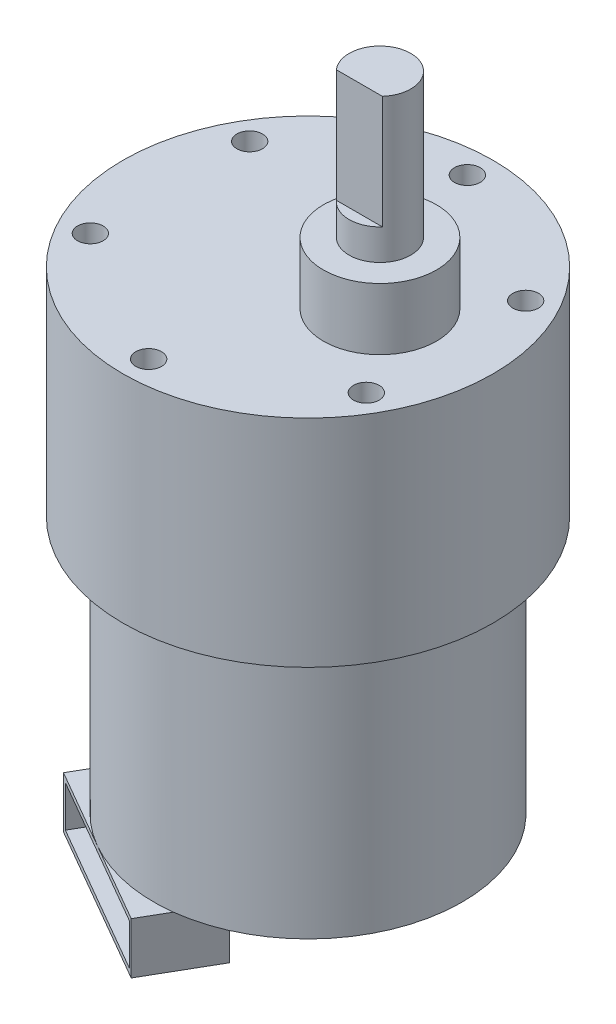
SolidWorks part; units mm, degrees
ref_plane "前视基准面" through (0, 0, 0) normal (0, 0, 1) x (1, 0, 0)
ref_plane "上视基准面" through (0, 0, 0) normal (0, 1, 0) x (1, 0, 0)
ref_plane "右视基准面" through (0, 0, 0) normal (1, 0, 0) x (0, 0, -1)
sketch "草图1" plane through (0, 0, 0) normal (0, 1, 0) x (1, 0, 0)
  circle A0 centre (0, 0) radius 15
  dimension "D1" = 30
extrude "凸台-拉伸1" add sketch "草图1" along normal blind 25
sketch "草图2" plane through (0, 25, 0) normal (0, 1, 0) x (1, 0, 0)
  circle A0 centre (0, 0) radius 18
  dimension "D1" = 36
extrude "凸台-拉伸2" add sketch "草图2" along normal blind 21
sketch "草图3" plane through (0, 46, 0) normal (0, 1, 0) x (1, 0, 0)
  circle A0 centre (7, 0) radius 5.5
  circle A1 centre (0, 0) radius 18 construction
  dimension "D1" = 11
  dimension "D2" = 11
extrude "凸台-拉伸3" add sketch "草图3" along normal blind 6
sketch "草图4" plane through (0, 52, 0) normal (0, 1, 0) x (1, 0, 0)
  circle A1 centre (7, 0) radius 3
  dimension "D1" = 6
extrude "凸台-拉伸4" add sketch "草图4" along normal blind 14
sketch "草图5" plane through (0, 66, 0) normal (0, 1, 0) x (1, 0, 0)
  line L0 (9.2361, -2) -> (4.7639, -2)
  circle A0 centre (7, 0) radius 3 construction
  arc A1 (4.7639, -2) -> (9.2361, -2) centre (7, 0) ccw
  dimension "D1" = 2
extrude "切除-拉伸1" cut sketch "草图5" against normal blind 11
sketch "草图6" plane through (0, 46, 0) normal (0, 1, 0) x (1, 0, 0)
  circle A0 centre (0, 0) radius 15.5 construction
  circle A1 centre (0, 15.5) radius 1.5
  circle A2 centre (13.4234, 7.75) radius 1.5
  circle A3 centre (13.4234, -7.75) radius 1.5
  circle A4 centre (0, -15.5) radius 1.5
  circle A5 centre (-13.4234, -7.75) radius 1.5
  circle A6 centre (-13.4234, 7.75) radius 1.5
  point P17 (0, 0)
  dimension "D1" = 31
  dimension "D2" = 3
  dimension "D3" = 6
hole_wizard "M3 螺纹孔1" positions "草图7" profile "草图8" tap size "M3" standard "GB"
sketch "草图7" plane through (0, 46, 0) normal (0, 1, 0) x (1, 0, 0)
  point P0 (0, 15.5)
  point P3 (-13.4234, 7.75)
  point P6 (-13.4234, -7.75)
  point P9 (0, -15.5)
  point P12 (13.4234, -7.75)
  point P15 (13.4234, 7.75)
sketch "草图8" plane through (0, 46, -15.5) normal (1, 0, 0) x (0, 0, 1)
  line L0 (0, 0) -> (0, 6.2511)
  line L1 (0, 6.2511) -> (1.25, 5.5)
  line L2 (1.25, 5.5) -> (1.25, 0)
  line L5 (1.25, 0) -> (0, 0)
  line L10 (0, 6.2511) -> (-1.25, 5.5) construction
  line L11 (0, -6.35) -> (0, 107.95) construction
  dimension "螺纹孔钻头直径" = 2.5
  dimension "螺纹孔钻头深度" = 5.5
  dimension "导头角度" = 118
cosmetic thread "孔螺蚊线1" parameters "D1"=6, "D2"=3
cosmetic thread "孔螺蚊线2" parameters "D1"=6, "D2"=3
cosmetic thread "孔螺蚊线3" parameters "D1"=6, "D2"=3
cosmetic thread "孔螺蚊线4" parameters "D1"=6, "D2"=3
cosmetic thread "孔螺蚊线5" parameters "D1"=6, "D2"=3
cosmetic thread "孔螺蚊线6" parameters "D1"=6, "D2"=3
sketch "草图9" plane through (0, 0, 0) normal (0, -1, 0) x (1, 0, 0)
  line L0 (-15.2942, 8.4904) -> (-11.7942, 2.4282)
  line L1 (-15.2942, 8.4904) -> (0.2942, 17.4904)
  line L2 (-11.7942, 2.4282) -> (3.7942, 11.4282)
  line L3 (0.2942, 17.4904) -> (3.7942, 11.4282)
  line L4 (0, 0) -> (-7.5, 12.9904) construction
  line L5 (0, 0) -> (0, 5.6928) construction
  circle A0 centre (0, 0) radius 15 construction
  dimension "D1" = 18
  dimension "D2" = 7
  dimension "D3" = 30
extrude "凸台-拉伸5" add sketch "草图9" along normal blind 5
sketch "草图10" plane through (0, 0, 0) normal (0, -1, 0) x (1, 0, 0)
  circle A0 centre (0, 0) radius 7
  dimension "D1" = 14
extrude "凸台-拉伸6" add sketch "草图10" along normal blind 5
sketch "草图11" plane through (-7.5, 0, 12.9904) normal (-0.5, 0, 0.866) x (0.866, 0, 0.5)
  line L10 (8.5, -0.5) -> (0, -0.5)
  line L11 (0, -0.5) -> (-8.5, -0.5)
  line L12 (-8.5, -0.5) -> (-8.5, -4.5)
  line L13 (-8.5, -4.5) -> (8.5, -4.5)
  line L14 (8.5, -4.5) -> (8.5, -0.5)
  line L15 (8.5, -0.5) -> (0, -0.5)
  line L16 (0, -0.5) -> (-8.5, -0.5)
  line L17 (-8.5, -0.5) -> (-8.5, -4.5)
  line L18 (-8.5, -4.5) -> (8.5, -4.5)
  line L19 (8.5, -4.5) -> (8.5, -0.5)
  dimension "D1" = 0.5
extrude "切除-拉伸2" cut sketch "草图11" against normal offset from surface (6 mm away) 1 up to face at (-4, -2.5, 6.9282)
sketch "草图12" plane through (-4.5, 0, 7.7942) normal (-0.5, 0, 0.866) x (0.866, 0, 0.5)
  line L0 (-7.7, -2.5) -> (-8.5, -2.5) construction
  line L1 (-7.7, -2.3) -> (-7.3, -2.3)
  line L2 (-7.7, -2.3) -> (-7.7, -2.7)
  line L3 (-7.7, -2.7) -> (-7.3, -2.7)
  line L4 (-7.3, -2.3) -> (-7.3, -2.7)
  line L5 (-8.5, -0.5) -> (-8.5, -4.5) construction
  line L6 (-4.7, -2.3) -> (-4.7, -2.7)
  line L7 (-4.7, -2.3) -> (-4.3, -2.3)
  line L8 (-4.3, -2.3) -> (-4.3, -2.7)
  line L9 (-4.7, -2.7) -> (-4.3, -2.7)
  line L10 (-1.7, -2.3) -> (-1.7, -2.7)
  line L11 (-1.7, -2.3) -> (-1.3, -2.3)
  line L12 (-1.3, -2.3) -> (-1.3, -2.7)
  line L13 (-1.7, -2.7) -> (-1.3, -2.7)
  line L14 (1.3, -2.3) -> (1.3, -2.7)
  line L15 (1.3, -2.3) -> (1.7, -2.3)
  line L16 (1.7, -2.3) -> (1.7, -2.7)
  line L17 (1.3, -2.7) -> (1.7, -2.7)
  line L18 (4.3, -2.3) -> (4.3, -2.7)
  line L19 (4.3, -2.3) -> (4.7, -2.3)
  line L20 (4.7, -2.3) -> (4.7, -2.7)
  line L21 (4.3, -2.7) -> (4.7, -2.7)
  line L22 (7.3, -2.3) -> (7.3, -2.7)
  line L23 (7.3, -2.3) -> (7.7, -2.3)
  line L24 (7.7, -2.3) -> (7.7, -2.7)
  line L25 (7.3, -2.7) -> (7.7, -2.7)
  line L26 (8.5, -0.5) -> (8.5, -4.5) construction
  dimension "D1" = 0.4
  dimension "D2" = 0.8
  dimension "D4" = 0.8
  dimension "D3" = 6
extrude "凸台-拉伸7" add sketch "草图12" along normal offset from surface (5 mm away) 1 up to face at (-7.5, -2.5, 12.9904)
